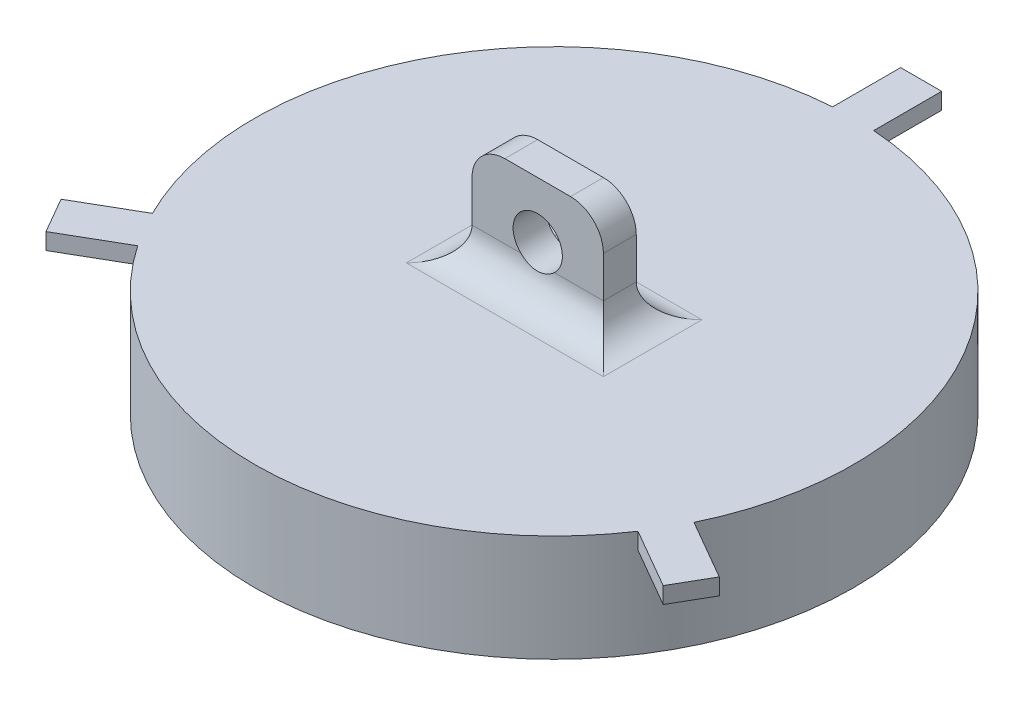
SolidWorks part; units mm, degrees
ref_plane "Спереди" through (0, 0, 0) normal (0, 0, 1) x (1, 0, 0)
ref_plane "Сверху" through (0, 0, 0) normal (0, 1, 0) x (1, 0, 0)
ref_plane "Справа" through (0, 0, 0) normal (1, 0, 0) x (0, 0, -1)
sketch "Sketch1" plane through (0, 0, 0) normal (0, 1, 0) x (1, 0, 0)
  circle A0 centre (0, 0) radius 18.25
  circle A1 centre (0, 0) radius 17.75
  dimension "D1" = 0.5
  dimension "D2" = 36.5
extrude "Boss-Extrude1" add sketch "Sketch1" along normal blind 6.5
sketch "Sketch2" plane through (0, 6.5, 0) normal (0, 1, 0) x (1, 0, 0)
  circle A0 centre (0, 0) radius 18.25
  circle A1 centre (0, 0) radius 18.25 construction
extrude "Boss-Extrude2" add sketch "Sketch2" against normal blind 1.5
sketch "Sketch3" plane through (0, 5, 0) normal (0, -1, 0) x (-1, 0, 0)
  line L0 (18.6228, -12.3184) -> (12.7874, -8.9493)
  line L5 (1.25, 22.3485) -> (-1.25, 22.3485)
  line L6 (1.25, 22.3485) -> (1.25, 15.6104)
  line L7 (1.25, 15.6104) -> (-1.25, 15.6104)
  line L8 (-1.25, 22.3485) -> (-1.25, 15.6104)
  line L9 (1.25, 22.3485) -> (-1.25, 15.6104) construction
  line L10 (1.25, 15.6104) -> (-1.25, 22.3485) construction
  line L11 (18.6228, -12.3184) -> (19.8728, -10.1533)
  line L12 (19.8728, -10.1533) -> (14.0374, -6.7842)
  line L13 (12.7874, -8.9493) -> (14.0374, -6.7842)
  line L14 (-20.086, -10.0302) -> (-14.2506, -6.6611)
  line L15 (-20.086, -10.0302) -> (-18.836, -12.1952)
  line L16 (-18.836, -12.1952) -> (-13.0006, -8.8262)
  line L17 (-14.2506, -6.6611) -> (-13.0006, -8.8262)
  point P0 (0, 0)
  point P1 (0, 18.9795)
  point P8 (0, 0)
  point P17 (-0.0711, 0)
  dimension "D1" = 3
extrude "Boss-Extrude3" add sketch "Sketch3" against normal blind 1 from offset 0.5 offset against normal yes
sketch "Sketch4" plane through (0, 5, 0) normal (0, -1, 0) x (-1, 0, 0)
  line L1 (-4, 1) -> (4, 1)
  line L2 (-4, 1) -> (-4, -1)
  line L3 (-4, -1) -> (4, -1)
  line L4 (4, 1) -> (4, -1)
  line L5 (-4, 1) -> (4, -1) construction
  line L6 (-4, -1) -> (4, 1) construction
  point P0 (0, 0)
extrude "Boss-Extrude4" add sketch "Sketch4" against normal blind 8
fillet "Fillet1" radius 2 4 edges at (4, 6.5, 0) (0, 6.5, -1) (-4, 6.5, 0) (0, 6.5, 1)
sketch "Sketch5" plane through (0, 0, 1) normal (0, 0, 1) x (1, 0, 0)
  circle A0 centre (0, 9.5978) radius 1.5
extrude "Cut-Extrude1" cut sketch "Sketch5" against normal through all both and the other way through all
fillet "Fillet2" radius 2 2 edges at (4, 13, 0) (-4, 13, 0)
